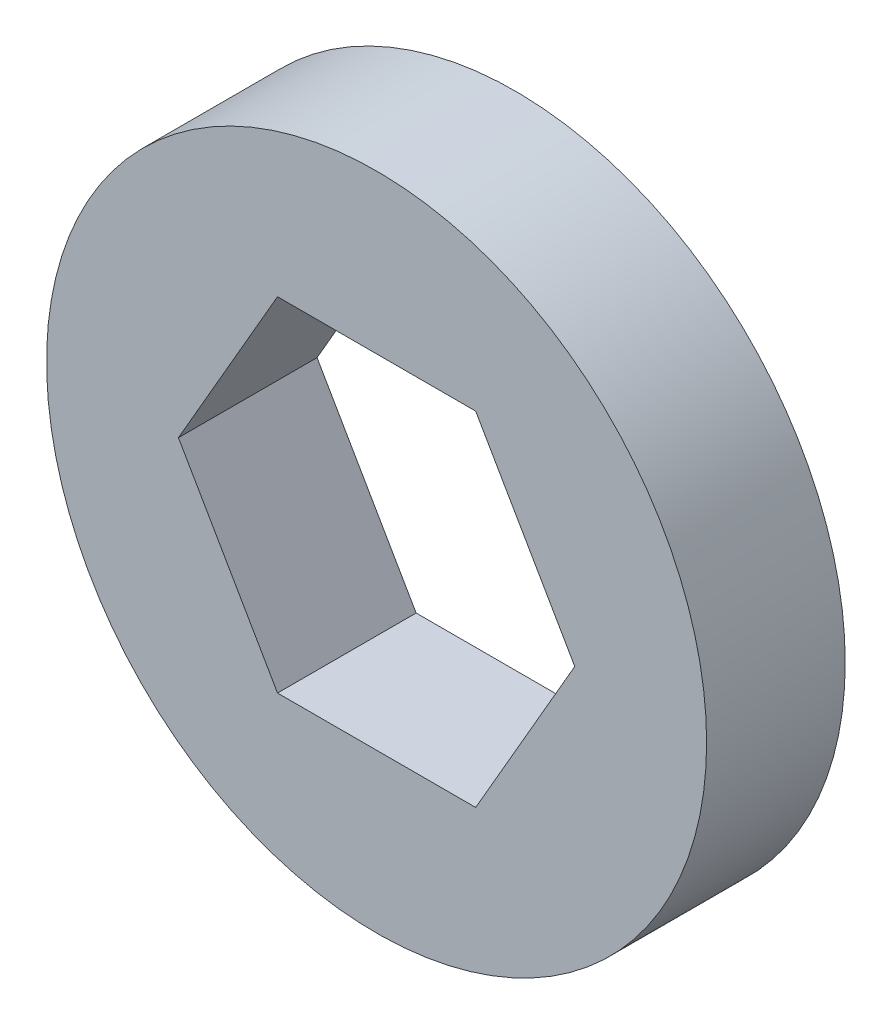
SolidWorks part; units mm, degrees
ref_plane "Front Plane" through (0, 0, 0) normal (0, 0, 1) x (1, 0, 0)
ref_plane "Top Plane" through (0, 0, 0) normal (0, 1, 0) x (1, 0, 0)
ref_plane "Right Plane" through (0, 0, 0) normal (1, 0, 0) x (0, 0, -1)
sketch "Sketch1" plane through (0, 0, 0) normal (0, 0, 1) x (1, 0, 0)
  line L1 (3.8128, -6.604) -> (7.6256, 0)
  line L2 (7.6256, 0) -> (3.8128, 6.604)
  line L3 (3.8128, 6.604) -> (-3.8128, 6.604)
  line L4 (-3.8128, 6.604) -> (-7.6256, 0)
  line L5 (-7.6256, 0) -> (-3.8128, -6.604)
  line L6 (-3.8128, -6.604) -> (3.8128, -6.604)
  circle A0 centre (0, 0) radius 6.604 construction
  circle A1 centre (0, 0) radius 12.7
  dimension "D2" = 25.4
  dimension "D1" = 13.208
extrude "Boss-Extrude1" add sketch "Sketch1" along normal blind 5.334
